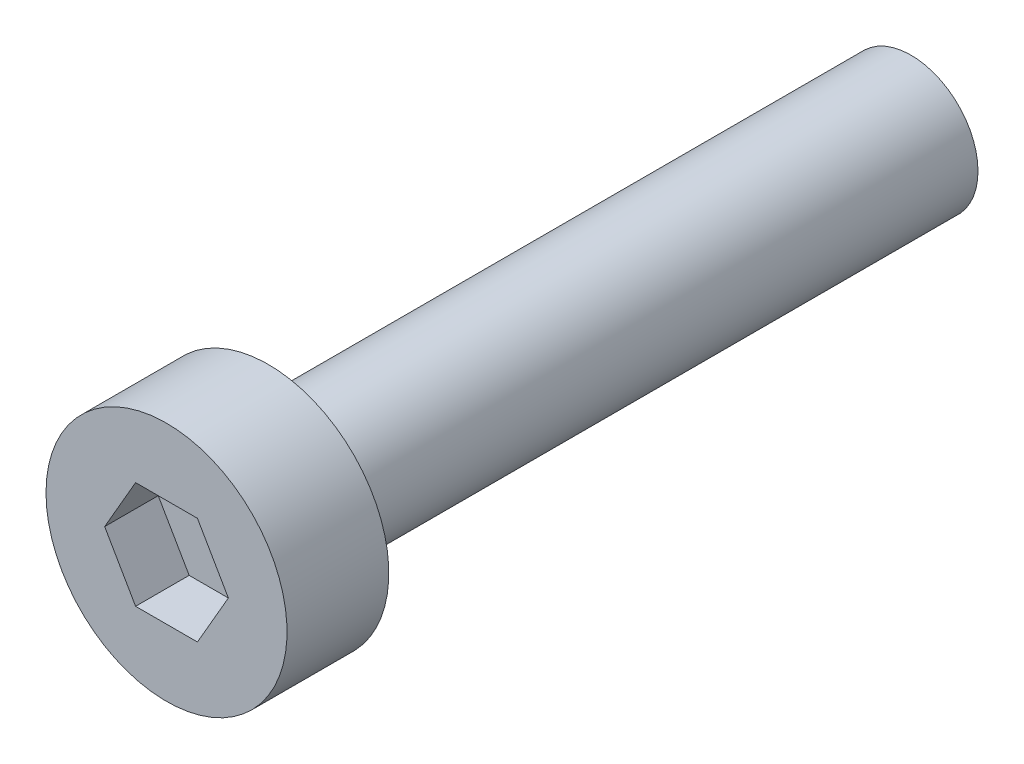
SolidWorks part; units mm, degrees
ref_plane "Plan de face" through (0, 0, 0) normal (0, 0, 1) x (1, 0, 0)
ref_plane "Plan de dessus" through (0, 0, 0) normal (0, 1, 0) x (1, 0, 0)
ref_plane "Plan de droite" through (0, 0, 0) normal (1, 0, 0) x (0, 0, -1)
sketch "Esquisse1" plane through (0, 0, 0) normal (0, 0, 1) x (1, 0, 0)
  circle A0 centre (0, 0) radius 1.25
  dimension "D1" = 2.5
extrude "Boss.-Extru.1" add sketch "Esquisse1" along normal blind 12
sketch "Esquisse2" plane through (0, 0, 12) normal (0, 0, 1) x (1, 0, 0)
  circle A0 centre (0, 0) radius 2.25
  dimension "D1" = 4.5
extrude "Boss.-Extru.2" add sketch "Esquisse2" along normal blind 1.9
sketch "Esquisse3" plane through (0, 0, 13.9) normal (0, 0, 1) x (1, 0, 0)
  line L1 (1.1547, 0) -> (0.5774, 1)
  line L2 (0.5774, 1) -> (-0.5774, 1)
  line L3 (-0.5774, 1) -> (-1.1547, 0)
  line L4 (-1.1547, 0) -> (-0.5774, -1)
  line L5 (-0.5774, -1) -> (0.5774, -1)
  line L6 (0.5774, -1) -> (1.1547, 0)
  circle A0 centre (0, 0) radius 1 construction
  dimension "D1" = 2
extrude "Enlèv. mat.-Extru.1" cut sketch "Esquisse3" against normal blind 1
